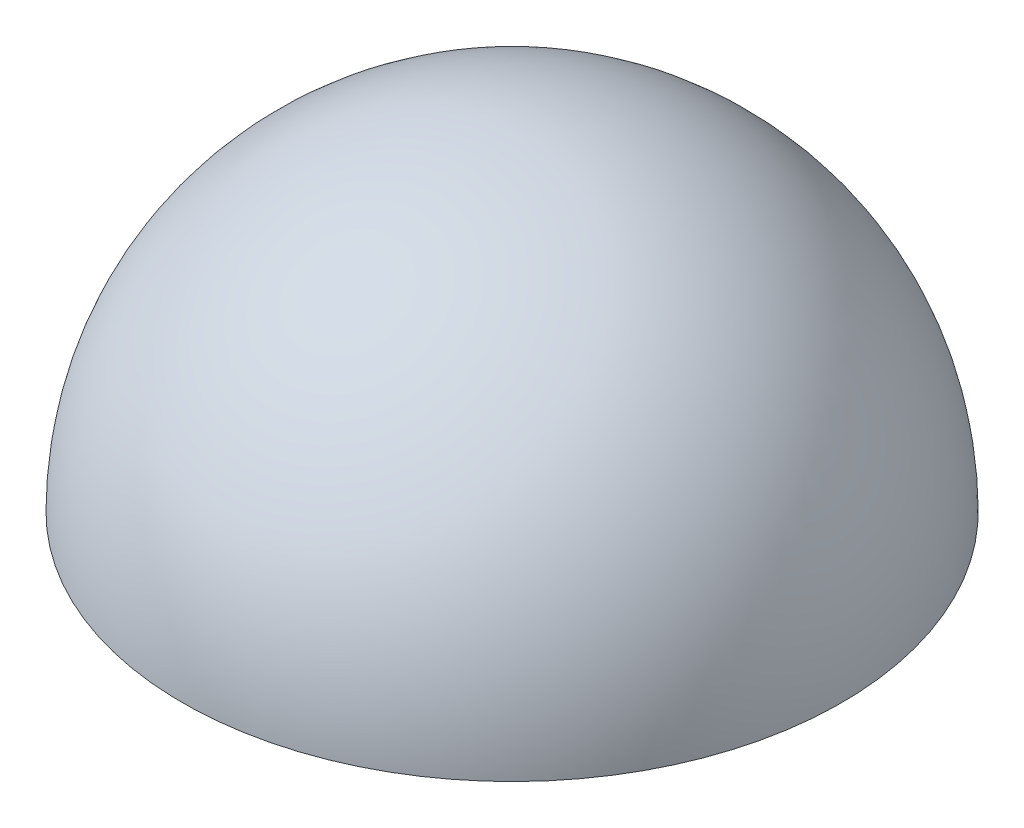
SolidWorks part; units mm, degrees
ref_plane "Front" through (0, 0, 0) normal (0, 0, 1) x (1, 0, 0)
ref_plane "Top" through (0, 0, 0) normal (0, 1, 0) x (1, 0, 0)
ref_plane "Right" through (0, 0, 0) normal (1, 0, 0) x (0, 0, -1)
sketch "Sketch1" plane through (0, 0, 0) normal (0, 1, 0) x (1, 0, 0)
  line L0 (-44.45, 0) -> (44.45, 0)
  arc A0 (44.45, 0) -> (-44.45, 0) centre (0, 0) ccw
revolve "Revolve1" add sketch "Sketch1" angle 180 about L0
